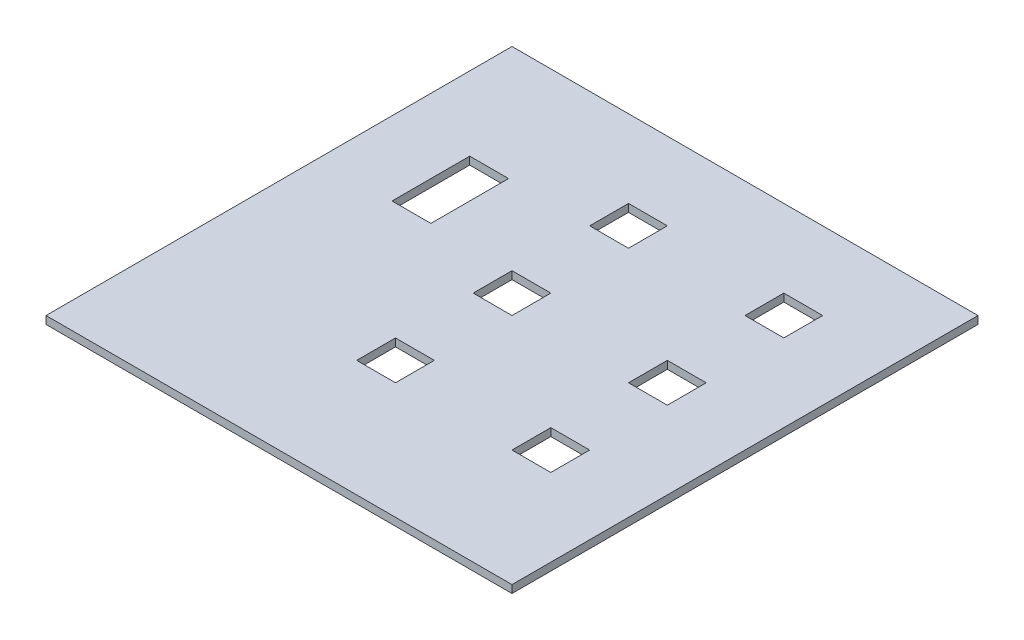
SolidWorks part; units mm, degrees
ref_plane "Front Plane" through (0, 0, 0) normal (0, 0, 1) x (1, 0, 0)
ref_plane "Top Plane" through (0, 0, 0) normal (0, 1, 0) x (1, 0, 0)
ref_plane "Right Plane" through (0, 0, 0) normal (1, 0, 0) x (0, 0, -1)
sketch "Sketch1" plane through (0, 0, 0) normal (0, 1, 0) x (1, 0, 0)
  line L1 (-152.4, -152.4) -> (152.4, -152.4)
  line L2 (-152.4, -152.4) -> (-152.4, 152.4)
  line L3 (-152.4, 152.4) -> (152.4, 152.4)
  line L4 (152.4, -152.4) -> (152.4, 152.4)
  line L5 (-152.4, -152.4) -> (152.4, 152.4) construction
  line L6 (-152.4, 152.4) -> (152.4, -152.4) construction
  point P0 (0, 0)
  dimension "D1" = 304.8
  dimension "D2" = 304.8
extrude "Boss-Extrude1" add sketch "Sketch1" along normal blind 5.08
sketch "Sketch2" plane through (0, 5.08, 0) normal (0, 1, 0) x (1, 0, 0)
  line L0 (152.4, 152.4) -> (-152.4, 152.4) construction
  line L1 (-25.4, 76.2) -> (0, 76.2)
  line L2 (-25.4, 76.2) -> (-25.4, 101.6)
  line L3 (-25.4, 101.6) -> (0, 101.6)
  line L4 (0, 76.2) -> (0, 101.6)
  line L5 (-25.4, 76.2) -> (0, 101.6) construction
  line L6 (-25.4, 101.6) -> (0, 76.2) construction
  line L7 (-152.4, 152.4) -> (-152.4, -152.4) construction
  point P0 (-12.7, 88.9)
  dimension "D1" = 25.4
  dimension "D2" = 25.4
  dimension "D3" = 50.8
  dimension "D4" = 127
extrude "Cut-Extrude1" cut sketch "Sketch2" against normal blind 5.08
pattern_linear "LPattern1" count 3 spacing 76.2 along (0, 0, 1) count 2 spacing 101.6 along (1, 0, 0) of "Cut-Extrude1"
sketch "Sketch3" plane through (0, 5.08, 0) normal (0, 1, 0) x (1, 0, 0)
  line L1 (-104.1075, 25.6495) -> (-78.7075, 25.6495)
  line L2 (-104.1075, 25.6495) -> (-104.1075, 76.4495)
  line L3 (-104.1075, 76.4495) -> (-78.7075, 76.4495)
  line L4 (-78.7075, 25.6495) -> (-78.7075, 76.4495)
  line L5 (-104.1075, 25.6495) -> (-78.7075, 76.4495) construction
  line L6 (-104.1075, 76.4495) -> (-78.7075, 25.6495) construction
  point P0 (-91.4075, 51.0495)
  dimension "D1" = 25.4
  dimension "D2" = 50.8
extrude "Cut-Extrude2" cut sketch "Sketch3" against normal blind 7.62
